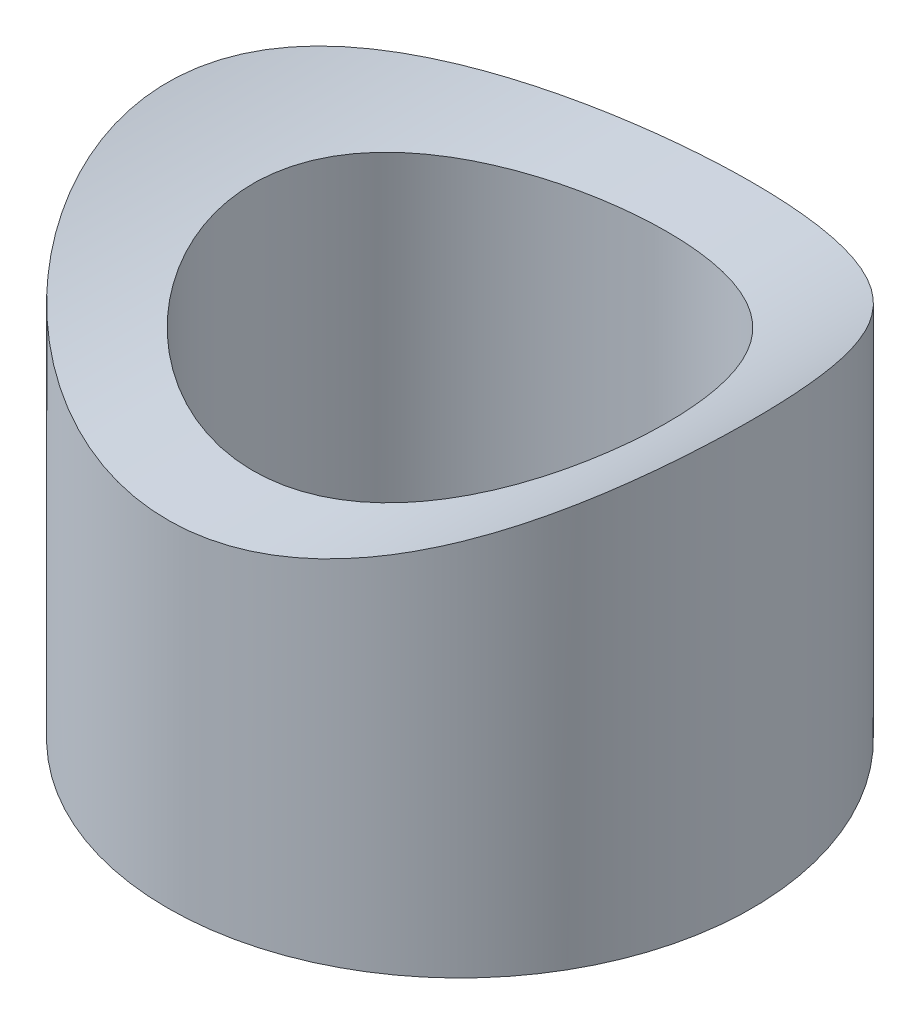
SolidWorks part; units mm, degrees
ref_plane "Front Plane" through (0, 0, 0) normal (0, 0, 1) x (1, 0, 0)
ref_plane "Top Plane" through (0, 0, 0) normal (0, 1, 0) x (1, 0, 0)
ref_plane "Right Plane" through (0, 0, 0) normal (1, 0, 0) x (0, 0, -1)
sketch "Sketch1" plane through (0, 0, 0) normal (0, 1, 0) x (1, 0, 0)
  circle A0 centre (0, 0) radius 6
  circle A1 centre (0, 0) radius 4.25
  dimension "D1" = 12
  dimension "D2" = 8.5
extrude "Boss-Extrude1" add sketch "Sketch1" along normal blind 6.9
sketch "Sketch2" plane through (0, 6.9, 0) normal (0, 1, 0) x (1, 0, 0)
  circle A0 centre (0, 0) radius 4.25 construction
  circle A1 centre (0, 0) radius 6
  circle A2 centre (0, 0) radius 6
  circle A3 centre (0, 0) radius 4.25
  dimension "D1" = 0
extrude "Boss-Extrude2" add sketch "Sketch2" along normal blind 4
sketch "Sketch3" plane through (0, 0, 0) normal (0, 0, 1) x (1, 0, 0)
  line L0 (0, 0) -> (0, 6.9) construction
  line L1 (-6, 0) -> (6, 0) construction
  line L2 (0, 6.9) -> (0, 17.9) construction
  circle A0 centre (0, 17.9) radius 11
  dimension "D1" = 6.9
  dimension "D2" = 11
extrude "Cut-Extrude1" cut sketch "Sketch3" against normal through all both and the other way through all
